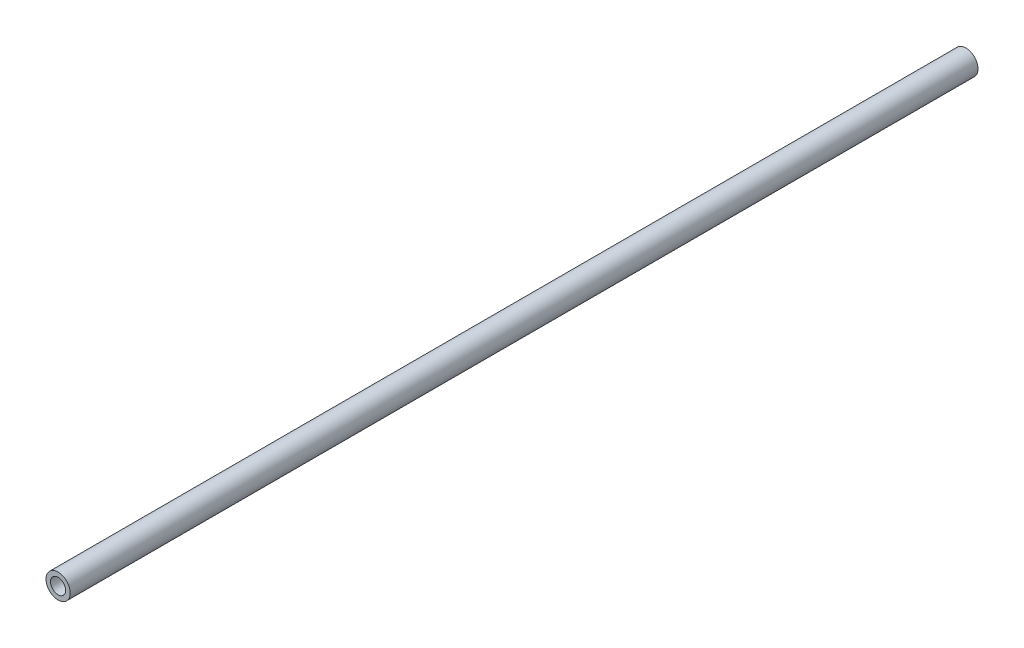
SolidWorks part; units mm, degrees
material "7075-O (SS)"
ref_plane "Front Plane" through (0, 0, 0) normal (0, 0, 1) x (1, 0, 0)
ref_plane "Top Plane" through (0, 0, 0) normal (0, 1, 0) x (1, 0, 0)
ref_plane "Right Plane" through (0, 0, 0) normal (1, 0, 0) x (0, 0, -1)
sketch "Sketch1" plane through (0, 0, 0) normal (0, 0, 1) x (1, 0, 0)
  circle A0 centre (0, 0) radius 8
  circle A1 centre (0, 0) radius 5
  dimension "D1" = 16
  dimension "D2" = 3
extrude "Boss-Extrude1" add sketch "Sketch1" along normal blind 600
